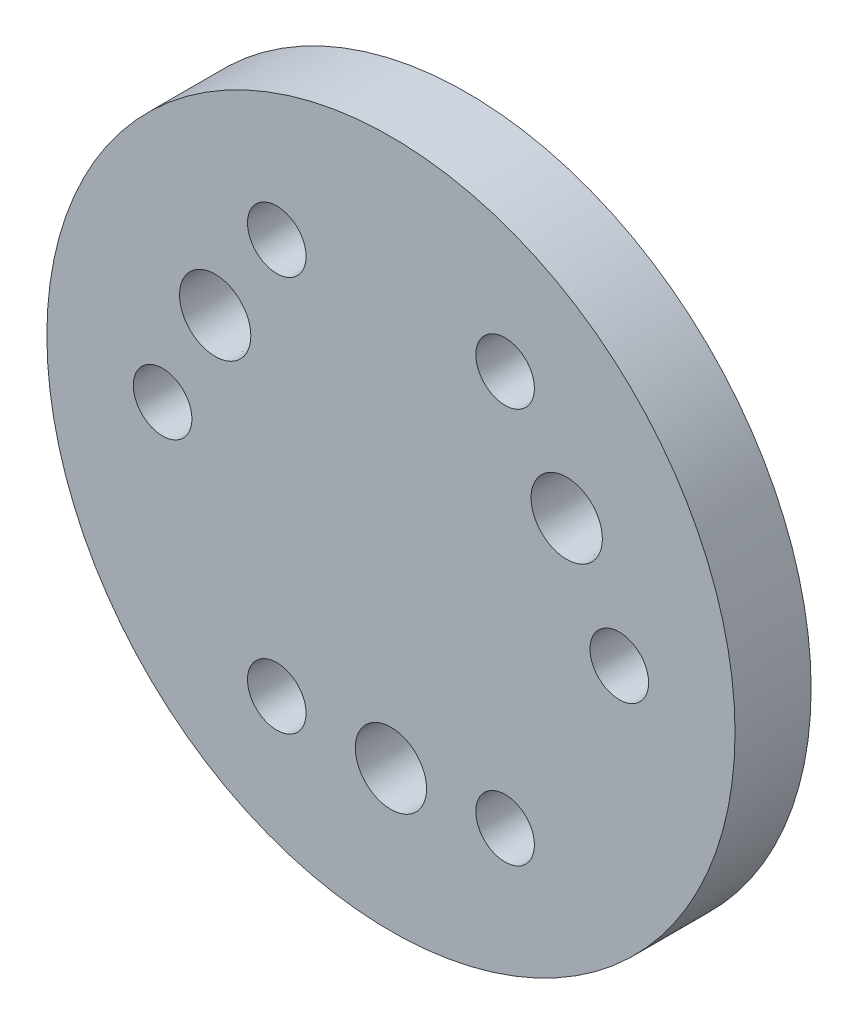
SolidWorks part; units mm, degrees
other "Markup1"
sketch "Sketch6" plane through (31.1257, -31.1257, 6.6) normal (0.5824, -0.4463, 0.6794) x (0.0162, 0.842, 0.5392)
ref_plane "Front Plane" through (0, 0, 0) normal (1, 0, 0) x (0, 1, 0)
ref_plane "Top Plane" through (0, 0, 0) normal (0, 0, 1) x (0, 1, 0)
ref_plane "Right Plane" through (0, 0, 0) normal (0, 1, 0) x (-1, 0, 0)
sketch "Sketch1" plane through (0, 0, 0) normal (0, 0, 1) x (0, 1, 0)
  circle A0 centre (0, 0) radius 27.125
  dimension "D1" = 54.25
extrude "Boss-Extrude1" add sketch "Sketch1" along normal blind 6
sketch "Sketch2" plane through (0, 0, 6) normal (0, 0, -1) x (1, 0, 0)
  circle A0 centre (0, 0) radius 16 construction
  circle A1 centre (0, 16) radius 2.6
  circle A2 centre (13.8564, -8) radius 2.6
  circle A3 centre (-13.8564, -8) radius 2.6
  circle A4 centre (0, 0) radius 18 construction
  circle A5 centre (-9, -15.5885) radius 2.1
  circle A11 centre (-18, 0) radius 2.1
  circle A12 centre (-9, 15.5885) radius 2.1
  circle A13 centre (9, 15.5885) radius 2.1
  circle A14 centre (18, 0) radius 2.1
  circle A15 centre (9, -15.5885) radius 2.1
  dimension "D1" = 32
  dimension "D2" = 5.2
  dimension "D5" = 4.2
  dimension "D4" = 36
  dimension "D3" = 3
  dimension "D6" = 6
extrude "Cut-Extrude1" cut sketch "Sketch2" against normal through all draft 2 from surface at 6 starting at face at (27.125, 0, 0) draft outward yes
equation "\"SunTeeth\"= 12"
equation "\"PlanetTeeth\" = 20"
equation "\"Module\" = 1"
equation "\"OrbitDiameter\"= \"SunTeeth\" * \"Module\" + \"PlanetTeeth\" * \"Module\""
equation "\"RingDiameter\"= ( \"SunTeeth\" + 2 * \"PlanetTeeth\" ) * \"Module\""
equation "\"BearingBore\" = 4"
equation "\"D1@Sketch2\"=\"OrbitDiameter\""
equation "\"D2@Sketch2\"=5.2"
equation "\"PressureAngle\" = 20deg"
equation "\"GearWidth\"=10"
equation "\"BearingDiameter\" = 13"
equation "\"ShaftDiameter\"= 6.5"
equation "\"D1@Sketch1\"=( \"SunTeeth\" + 2 * \"PlanetTeeth\" ) * \"Module\"+ 2.25*\"Module\""
